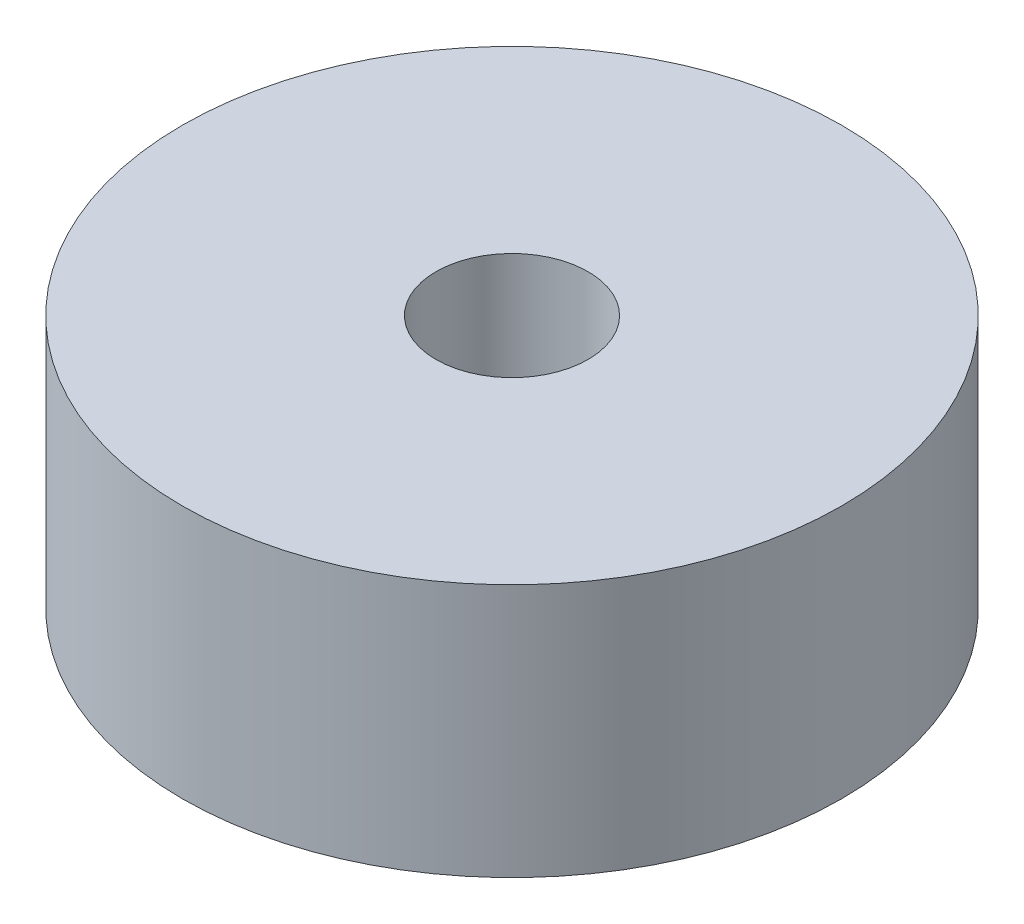
SolidWorks part; units mm, degrees
ref_plane "Front Plane" through (0, 0, 0) normal (0, 0, 1) x (1, 0, 0)
ref_plane "Top Plane" through (0, 0, 0) normal (0, 1, 0) x (1, 0, 0)
ref_plane "Right Plane" through (0, 0, 0) normal (1, 0, 0) x (0, 0, -1)
sketch "Sketch1" plane through (0, 0, 0) normal (0, 1, 0) x (1, 0, 0)
  circle A0 centre (0, 0) radius 6.5
  circle A1 centre (0, 0) radius 1.5
  dimension "D1" = 13
  dimension "D2" = 3
extrude "Boss-Extrude1" add sketch "Sketch1" along normal blind 5
